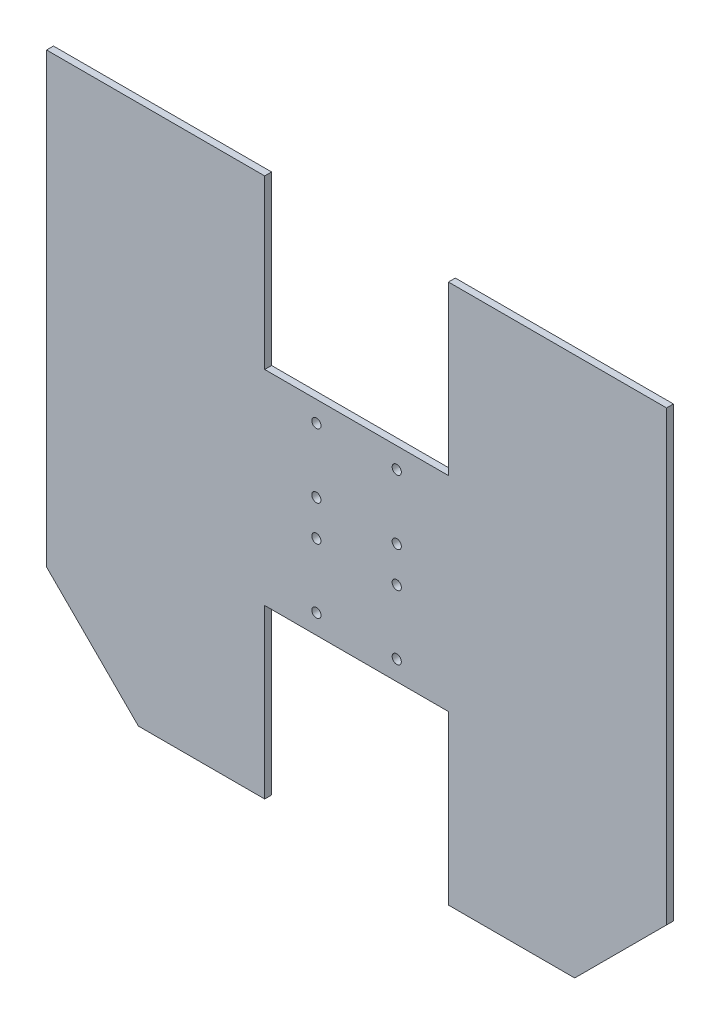
SolidWorks part; units mm, degrees
ref_plane "Plan de face" through (0, 0, 0) normal (0, 0, 1) x (1, 0, 0)
ref_plane "Plan de dessus" through (0, 0, 0) normal (0, 1, 0) x (1, 0, 0)
ref_plane "Plan de droite" through (0, 0, 0) normal (1, 0, 0) x (0, 0, -1)
sketch "Esquisse1" plane through (0, 0, 0) normal (0, 0, 1) x (1, 0, 0)
  line L0 (-40, 117.5) -> (-40, 44.5)
  line L1 (135, -117.5) -> (40, -117.5)
  line L2 (135, -117.5) -> (135, 117.5)
  line L3 (135, 117.5) -> (40, 117.5)
  line L4 (-135, -117.5) -> (-135, 117.5)
  line L5 (135, -117.5) -> (-135, 117.5) construction
  line L6 (135, 117.5) -> (-135, -117.5) construction
  line L7 (-40, 44.5) -> (40, 44.5)
  line L8 (40, 44.5) -> (40, 117.5)
  line L9 (-135, 117.5) -> (-40, 117.5)
  line L10 (-154.9552, 0) -> (164.134, 0) construction
  line L11 (40, -44.5) -> (40, -117.5)
  line L12 (-40, -44.5) -> (40, -44.5)
  line L13 (-40, -117.5) -> (-40, -44.5)
  line L14 (-40, -117.5) -> (-135, -117.5)
  point P0 (0, 0)
  point P8 (0, 44.5)
  dimension "D1" = 270
  dimension "D2" = 235
  dimension "D3" = 80
  dimension "D4" = 73
  dimension "D5" = 73
extrude "Boss.-Extru.1" add sketch "Esquisse1" along normal blind 3
sketch "Esquisse2" plane through (0, 0, 3) normal (0, 0, 1) x (1, 0, 0)
  circle A0 centre (-17.5, -35.98) radius 2
  circle A1 centre (17.5, -35.98) radius 2
  circle A2 centre (-17.5, -7.98) radius 2
  circle A3 centre (-17.5, 7.5) radius 2
  circle A4 centre (17.5, 7.5) radius 2
  circle A5 centre (17.5, -7.98) radius 2
  circle A6 centre (-17.5, 35.5) radius 2
  circle A7 centre (17.5, 35.5) radius 2
  dimension "D1" = 4
extrude "Enlèv. mat.-Extru.1" cut sketch "Esquisse2" against normal through all
chamfer "Chanfrein1" distance 40 angle 45 2 edges at (135, -117.5, 1.5) (-135, -117.5, 1.5)
